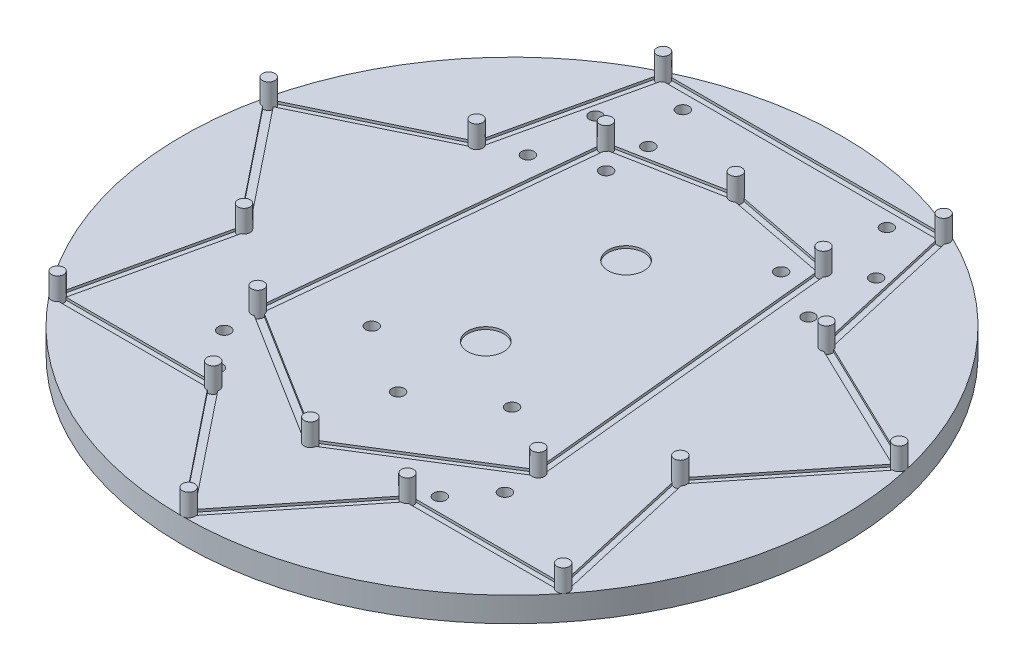
SolidWorks part; units mm, degrees
ref_plane "Front Plane" through (0, 0, 0) normal (0, 0, 1) x (1, 0, 0)
ref_plane "Top Plane" through (0, 0, 0) normal (0, 1, 0) x (1, 0, 0)
ref_plane "Right Plane" through (0, 0, 0) normal (1, 0, 0) x (0, 0, -1)
sketch "Sketch1" plane through (0, 0, 0) normal (0, 1, 0) x (1, 0, 0)
  circle A0 centre (0, 0) radius 132.5
  dimension "D1" = 265
extrude "Boss-Extrude1" add sketch "Sketch1" against normal blind 10
sketch "Sketch2" plane through (0, 0, 0) normal (0, 1, 0) x (1, 0, 0)
  line L0 (-102.3417, -81.6148) -> (102.3417, -81.6148)
  line L1 (102.3417, -81.6148) -> (56.7954, 117.9368)
  line L2 (56.7954, 117.9368) -> (-127.6181, 29.128)
  line L3 (-127.6181, 29.128) -> (0, -130.9)
  line L4 (0, -130.9) -> (127.6181, 29.128)
  line L5 (127.6181, 29.128) -> (-56.7954, 117.9368)
  line L6 (-56.7954, 117.9368) -> (-102.3417, -81.6148)
  line L7 (56.7954, 117.9368) -> (56.7954, 63.2344) construction
  line L8 (0, -130.9) -> (102.3417, -81.6148)
  line L9 (102.3417, -81.6148) -> (127.6181, 29.128)
  line L10 (127.6181, 29.128) -> (56.7954, 117.9368)
  line L11 (56.7954, 117.9368) -> (-56.7954, 117.9368)
  line L12 (-56.7954, 117.9368) -> (-127.6181, 29.128)
  line L13 (-127.6181, 29.128) -> (-102.3417, -81.6148)
  line L14 (-102.3417, -81.6148) -> (0, -130.9)
  line L15 (-56.7954, 117.9368) -> (-56.7954, 63.2344) construction
  line L16 (-56.7954, 90.5856) -> (56.7954, 90.5856) construction
  line L17 (-56.7954, 63.2344) -> (-56.7954, -119.7102) construction
  line L18 (0, -130.9) -> (0, -10.6142)
  line L19 (-35.4113, 73.5324) -> (-35.4113, 107.6388) construction
  line L20 (56.7954, -119.7102) -> (56.7954, 46.1812) construction
  line L21 (-56.7954, -46.1145) -> (56.7954, -46.1145)
  line L22 (56.7954, -10.6142) -> (-56.7954, -10.6142) construction
  line L23 (56.7954, -10.6142) -> (-56.7954, -81.6148) construction
  line L24 (0, -81.6148) -> (-56.7954, -46.1145) construction
  line L25 (56.7954, -81.6148) -> (-56.7954, -10.6142) construction
  line L26 (0, -81.6148) -> (56.7954, -46.1145) construction
  line L27 (56.7954, -46.1145) -> (0, -10.6142) construction
  line L28 (0, -10.6142) -> (-56.7954, -46.1145) construction
  line L29 (35.4113, 107.6388) -> (35.4113, 73.5324) construction
  circle A0 centre (0, 0) radius 130.9
  circle A1 centre (0, 0) radius 117.9368 construction
  circle A3 centre (0, 46.1812) radius 56.7954
  arc A4 (-0.0451, -132.5) -> (-54.8645, -120.6074) centre (-28.3977, -130.9) ccw
  arc A5 (54.8645, -120.6074) -> (0.0451, -132.5) centre (28.3977, -130.9) ccw
  circle A6 centre (0, 0) radius 132.5
  circle A7 centre (0, 0) radius 132.5 construction
  circle A9 centre (0, 46.1812) radius 7.27
  arc A10 (-56.7673, 119.7235) -> (56.7673, 119.7235) centre (0, 117.9368) ccw
  point P7 (35.4113, 90.5856)
  point P31 (0, -130.9)
  point P33 (-35.4113, 90.5856)
  point P40 (0, -46.1145)
  point P50 (-28.3977, -63.8647)
  point P54 (28.3977, -28.3643)
  point P55 (28.3977, -63.8647)
  point P56 (-28.3977, -28.3643)
  point P57 (-35.4113, 90.5856)
  point P60 (35.4113, 90.5856)
  dimension "D1" = 261.8
  dimension "D2" = 14.54
sketch "Sketch4" plane through (0, 0, 0) normal (0, 1, 0) x (1, 0, 0)
  line L4 (0, -130.9) -> (0, -10.6142) construction
  line L11 (-0.5, -123.3637) -> (-0.5, -46.6145)
  line L12 (0.5, -123.3637) -> (0.5, -46.6145)
  line L13 (56.7954, -46.1145) -> (-56.7954, -46.1145) construction
  line L14 (56.7954, -46.6145) -> (0.5, -46.6145)
  line L15 (56.7954, -45.6145) -> (0.5, -45.6145)
  line L16 (-0.5, -46.6145) -> (-56.7954, -46.6145)
  line L17 (-0.5, -45.6145) -> (-0.5, -11.112)
  line L18 (-0.5, -45.6145) -> (-56.7954, -45.6145)
  line L19 (0.5, -45.6145) -> (0.5, -11.112)
  circle A11 centre (0, 46.1812) radius 7.27
  circle A42 centre (0, 0) radius 130.9 construction
  arc A43 (54.8645, -120.6074) -> (0.0451, -132.5) centre (28.3977, -130.9) ccw construction
  arc A44 (54.2425, -119.1325) -> (0, -130.9) centre (28.3977, -130.9) ccw construction
  arc A45 (54.6976, -118.9253) -> (0.5, -123.3637) centre (28.3977, -130.9) ccw
  arc A46 (53.7875, -119.3397) -> (0.5, -130.9) centre (28.3977, -130.9) ccw
  arc A47 (53.7875, -119.3397) -> (54.6976, -118.9253) centre (54.2425, -119.1325) ccw
  arc A48 (-0.5, -130.9) -> (0.5, -130.9) centre (0, -130.9) ccw
  arc A49 (-0.5, -130.9) -> (0.5, -130.9) centre (0, -130.9) ccw
  arc A51 (56.7954, -46.6145) -> (56.7954, -45.6145) centre (56.7954, -46.1145) ccw
  arc A52 (-56.7954, -45.6145) -> (-56.7954, -46.6145) centre (-56.7954, -46.1145) ccw
  arc A53 (-54.2425, -119.1325) -> (0, -130.9) centre (-28.3977, -130.9) cw construction
  arc A54 (-53.7875, -119.3397) -> (-54.6976, -118.9253) centre (-54.2425, -119.1325) cw
  arc A55 (-54.6976, -118.9253) -> (-0.5, -123.3637) centre (-28.3977, -130.9) cw
  arc A56 (-53.7875, -119.3397) -> (-0.5, -130.9) centre (-28.3977, -130.9) cw
  arc A57 (-44.0241, 81.2675) -> (44.0241, 81.2675) centre (0, 46.1812) ccw
  arc A58 (0.5, -11.112) -> (44.6715, 82.059) centre (0, 46.1812) ccw
  arc A59 (56.7954, 117.9368) -> (-56.7954, 117.9368) centre (0, 117.9368) cw construction
  arc A60 (-57.2954, 117.9368) -> (-44.6715, 82.059) centre (0, 117.9368) ccw
  arc A61 (-56.2954, 117.9368) -> (-44.0241, 82.8505) centre (0, 117.9368) ccw
  arc A62 (-56.2954, 117.9368) -> (-57.2954, 117.9368) centre (-56.7954, 117.9368) ccw
  arc A63 (57.2954, 117.9368) -> (56.2954, 117.9368) centre (56.7954, 117.9368) ccw
  arc A64 (-56.7673, 119.7235) -> (56.7673, 119.7235) centre (0, 117.9368) ccw construction
  arc A65 (-44.0241, 81.2675) -> (44.0241, 81.2675) centre (0, 117.9368) ccw
  arc A66 (-44.6715, 82.059) -> (-0.5, -11.112) centre (0, 46.1812) ccw
  arc A67 (-43.3815, 82.059) -> (43.3815, 82.059) centre (0, 117.9368) ccw
  arc A68 (44.6715, 82.059) -> (57.2954, 117.9368) centre (0, 117.9368) ccw
  arc A69 (44.0241, 82.8505) -> (-44.0241, 82.8505) centre (0, 46.1812) ccw
  arc A70 (44.0241, 82.8505) -> (56.2954, 117.9368) centre (0, 117.9368) ccw
  arc A71 (43.3815, 82.059) -> (-43.3815, 82.059) centre (0, 46.1812) ccw
  circle A72 centre (0, 0) radius 132.5
  circle A73 centre (0, 46.1812) radius 56.2954
  point P0 (54.2425, -119.1325)
  point P1 (22.3771, -103.1479)
  point P16 (0, -70.7571)
  point P21 (0, -46.1145)
  point P42 (0, 61.1414)
  dimension "D1" = 1
  dimension "D2" = 1
  dimension "D3" = 1
  dimension "D4" = 1
  dimension "D5" = 1
  dimension "D6" = 14.54
extrude "Cut-Extrude2" cut sketch "Sketch4" against normal blind 1 contours A65 A73 A67 | A70 A69 A61 A62 A60 A66 L17 L18 A52 L16 L11 A55 A54 A56 A48 A46 A47 A45 L12 L14 A51 L15 L19 A58 A68 A63 A73 A57 A71 | A11
sketch "Sketch5" plane through (0, 0, 0) normal (0, 1, 0) x (1, 0, 0)
  line L0 (-102.3417, -81.6148) -> (102.3417, -81.6148) construction
  line L1 (0.2169, -131.3505) -> (102.5587, -82.0653)
  line L2 (102.8292, -81.7261) -> (128.1055, 29.0167)
  line L3 (128.009, 29.4397) -> (57.1863, 118.2486)
  line L4 (56.7954, 118.4368) -> (-56.7954, 118.4368)
  line L5 (-57.1863, 118.2486) -> (-128.009, 29.4397)
  line L6 (-128.1055, 29.0167) -> (-102.8292, -81.7261)
  line L7 (-102.5587, -82.0653) -> (-0.2169, -131.3505)
  line L9 (102.3417, -79.3678) -> (126.6431, 27.1035)
  line L10 (125.8613, 30.529) -> (57.7703, 115.9124)
  line L11 (54.6047, 117.4368) -> (-54.6047, 117.4368)
  line L15 (-101.7148, -81.1148) -> (-40.3419, -81.1148)
  line L16 (-100.1511, -82.1148) -> (-39.5444, -82.1148)
  line L17 (102.3417, -81.6148) -> (56.7954, 117.9368) construction
  line L19 (102.3417, -79.3678) -> (88.8555, -20.2807)
  line L20 (56.7954, 117.9368) -> (-127.6181, 29.128) construction
  line L22 (54.6047, 117.4368) -> (0, 91.1406)
  line L23 (-127.6181, 29.128) -> (0, -130.9) construction
  line L25 (-126.6431, 27.1035) -> (-88.8555, -20.2807)
  line L26 (0, -130.9) -> (127.6181, 29.128) construction
  line L28 (1.7568, -129.499) -> (39.5444, -82.1148)
  line L29 (127.6181, 29.128) -> (-56.7954, 117.9368) construction
  line L31 (125.8613, 30.529) -> (71.2566, 56.8252)
  line L32 (-102.3417, -81.6148) -> (-56.7954, 117.9368) construction
  line L33 (-102.3417, -79.3678) -> (-88.8555, -20.2807)
  line L36 (-57.7703, 115.9124) -> (-125.8613, 30.529)
  line L37 (-56.7047, 117.2486) -> (-57.0518, 116.8133) [skipped]
  line L38 (56.4474, 117.2143) -> (1.1524, 90.5856)
  line L39 (126.8362, 28.9495) -> (71.5412, 55.5782)
  line L40 (1.7568, -129.499) -> (100.1511, -82.1148)
  line L41 (101.7148, -81.1148) -> (88.058, -21.2807)
  line L42 (0.2169, -130.2406) -> (0.7185, -129.999) [skipped]
  line L43 (0, -130.0981) -> (38.2654, -82.1148)
  line L44 (-101.7148, -81.1148) -> (-88.058, -21.2807)
  line L45 (-100.1511, -82.1148) -> (-1.7568, -129.499)
  line L46 (-101.6909, -81.3733) -> (-101.1894, -81.6148) [skipped]
  line L47 (-126.6431, 27.1035) -> (-102.3417, -79.3678)
  line L48 (-127.0234, 28.7698) -> (-126.8996, 28.227) [skipped]
  line L49 (-126.8362, 28.9495) -> (-88.5709, -19.0337)
  line L50 (88.8555, -20.2807) -> (126.6431, 27.1035)
  line L51 (87.7734, -20.0337) -> (70.3888, 56.1332)
  line L52 (88.5709, -19.0337) -> (126.8362, 28.9495)
  line L53 (88.5709, -19.0337) -> (71.5412, 55.5782)
  line L54 (40.3419, -81.1148) -> (88.058, -21.2807)
  line L55 (39.5444, -82.1148) -> (100.1511, -82.1148)
  line L56 (39.0628, -81.1148) -> (87.7734, -20.0337)
  line L57 (40.3419, -81.1148) -> (101.7148, -81.1148)
  line L58 (-38.2654, -82.1148) -> (38.2654, -82.1148)
  line L59 (-39.5444, -82.1148) -> (-1.7568, -129.499)
  line L60 (-39.0628, -81.1148) -> (39.0628, -81.1148)
  line L61 (-38.2654, -82.1148) -> (0, -130.0981)
  line L62 (-87.7734, -20.0337) -> (-70.3888, 56.1332)
  line L63 (-88.058, -21.2807) -> (-40.3419, -81.1148)
  line L64 (-87.7734, -20.0337) -> (-39.0628, -81.1148)
  line L65 (-88.5709, -19.0337) -> (-71.5412, 55.5782)
  line L66 (-71.5412, 55.5782) -> (-126.8362, 28.9495)
  line L67 (-70.1042, 57.3802) -> (-56.4474, 117.2143)
  line L68 (-71.2566, 56.8252) -> (-125.8613, 30.529)
  line L69 (-71.2566, 56.8252) -> (-57.7703, 115.9124)
  line L70 (0, 90.0307) -> (-70.3888, 56.1332)
  line L71 (0, 91.1406) -> (-54.6047, 117.4368)
  line L72 (-1.1524, 90.5856) -> (-70.1042, 57.3802)
  line L73 (-1.1524, 90.5856) -> (-56.4474, 117.2143)
  line L74 (70.3888, 56.1332) -> (0, 90.0307)
  line L75 (71.2566, 56.8252) -> (57.7703, 115.9124)
  line L76 (70.1042, 57.3802) -> (1.1524, 90.5856)
  line L77 (70.1042, 57.3802) -> (56.4474, 117.2143)
  circle A0 centre (0, 0) radius 132.5
  circle A2 centre (0, 0) radius 117.4368 construction
  arc A3 (-102.8292, -81.7261) -> (-102.5587, -82.0653) centre (-102.3417, -81.6148) ccw
  arc A5 (-128.009, 29.4397) -> (-128.1055, 29.0167) centre (-127.6181, 29.128) ccw
  arc A8 (-57.1863, 118.2486) -> (-56.7954, 118.4368) centre (-56.7954, 117.9368) cw
  arc A9 (56.7954, 118.4368) -> (57.1863, 118.2486) centre (56.7954, 117.9368) cw
  arc A12 (128.1055, 29.0167) -> (128.009, 29.4397) centre (127.6181, 29.128) ccw
  arc A13 (102.8292, -81.7261) -> (102.5587, -82.0653) centre (102.3417, -81.6148) cw
  arc A16 (-0.2169, -131.3505) -> (0.2169, -131.3505) centre (0, -130.9) ccw
  arc A18 (102.5587, -82.0653) -> (102.8292, -81.7261) centre (102.3417, -81.6148) ccw
  arc A20 (57.1863, 118.2486) -> (56.7954, 118.4368) centre (56.7954, 117.9368) ccw
  arc A21 (57.1863, 118.2486) -> (56.7954, 118.4368) centre (56.7954, 117.9368) ccw
  arc A22 (-128.009, 29.4397) -> (-128.1055, 29.0167) centre (-127.6181, 29.128) ccw
  arc A23 (-128.009, 29.4397) -> (-128.1055, 29.0167) centre (-127.6181, 29.128) ccw
  arc A24 (-0.2169, -131.3505) -> (0.2169, -131.3505) centre (0, -130.9) ccw
  arc A25 (-0.2169, -131.3505) -> (0.2169, -131.3505) centre (0, -130.9) ccw
  arc A26 (128.1055, 29.0167) -> (128.009, 29.4397) centre (127.6181, 29.128) ccw
  arc A27 (128.1055, 29.0167) -> (128.009, 29.4397) centre (127.6181, 29.128) ccw
  arc A28 (-56.7954, 118.4368) -> (-57.1863, 118.2486) centre (-56.7954, 117.9368) ccw
  arc A29 (-56.2954, 117.9368) -> (-57.2954, 117.9368) centre (-56.7954, 117.9368) ccw construction
  arc A30 (-102.8292, -81.7261) -> (-102.5587, -82.0653) centre (-102.3417, -81.6148) ccw
  arc A31 (-56.7954, 118.4368) -> (-57.1863, 118.2486) centre (-56.7954, 117.9368) ccw
  arc A32 (102.5587, -82.0653) -> (102.8292, -81.7261) centre (102.3417, -81.6148) ccw
  arc A33 (-102.8292, -81.7261) -> (-102.5587, -82.0653) centre (-102.3417, -81.6148) ccw
  point P45 (0, -130.345)
  point P52 (0, -81.6148)
  point P57 (79.5686, 18.161)
  point P65 (-35.4113, 73.5324)
  point P73 (-63.809, -50.886)
  point P81 (63.809, -50.886)
  point P89 (35.4113, 73.5324)
  point P100 (-79.5686, 18.161)
  arc M31 (-44.0241, 82.8505) -> (44.0241, 82.8505) centre (0, 46.1812) cw
  arc M32 (44.0241, 82.8505) -> (56.2954, 117.9368) centre (0, 117.9368) ccw
  arc M33 (56.2954, 117.9368) -> (57.2954, 117.9368) centre (56.7954, 117.9368) cw
  arc M34 (57.2954, 117.9368) -> (44.6715, 82.059) centre (0, 117.9368) cw
  arc M35 (44.6715, 82.059) -> (0.5, -11.112) centre (0, 46.1812) cw
  line M40 (0.5, -46.6145) -> (0.5, -123.3637)
  arc M41 (0.5, -123.3637) -> (54.6976, -118.9253) centre (28.3977, -130.9) cw
  arc M43 (53.7875, -119.3397) -> (0.5, -130.9) centre (28.3977, -130.9) ccw
  arc M44 (0.5, -130.9) -> (-0.5, -130.9) centre (0, -130.9) cw
  arc M45 (-0.5, -130.9) -> (-53.7875, -119.3397) centre (-28.3977, -130.9) ccw
  arc M47 (-54.6976, -118.9253) -> (-0.5, -123.3637) centre (-28.3977, -130.9) cw
  line M48 (-0.5, -123.3637) -> (-0.5, -46.6145)
  arc M53 (-0.5, -11.112) -> (-44.6715, 82.059) centre (0, 46.1812) cw
  arc M54 (-44.6715, 82.059) -> (-57.2954, 117.9368) centre (0, 117.9368) cw
  arc M55 (-57.2954, 117.9368) -> (-56.2954, 117.9368) centre (-56.7954, 117.9368) cw
  arc M56 (-56.2954, 117.9368) -> (-44.0241, 82.8505) centre (0, 117.9368) ccw
  dimension "D2" = 0.5
  dimension "D1" = 1
extrude "Cut-Extrude3" cut sketch "Sketch5" against normal blind 1 contours A13 L2 A12 L3 L77 L76 L74 L51 L56 L60 L58 L43 L28 L55 L40 L1 L57 L54 L41 L19 L50 L9 L52 L53 L39 L31 L75 L10 M33 M34 M35 M40 M41 | L43 L1 L40 L28 M43 M44 | L61 L59 L45 L7 M45 M44 | L5 A5 L6 A3 L7 L45 L16 L59 L61 L58 L60 L64 L62 L70 L72 L67 L44 L63 L15 L47 L25 L33 L66 L65 L49 L69 L68 L36 M47 M48 M53 M54 M55 | L76 L38 L22 L71 L73 L72 L70 L74 M35 M31 M53 | L73 L71 L11 L22 L38 L4 M31 M32 M33 M55 M56
sketch "Sketch6" plane through (0, -1, 0) normal (0, 1, 0) x (1, 0, 0)
  line L0 (0, -130.9) -> (127.6181, 29.128) construction
  line L1 (127.6181, 29.128) -> (-56.7954, 117.9368) construction
  line L2 (-56.7954, 117.9368) -> (-102.3417, -81.6148) construction
  line L3 (-102.3417, -81.6148) -> (0, -130.9) construction
  line L4 (0, -130.9) -> (102.3417, -81.6148) construction
  line L5 (102.3417, -81.6148) -> (127.6181, 29.128) construction
  line L6 (127.6181, 29.128) -> (56.7954, 117.9368) construction
  line L7 (56.7954, 117.9368) -> (-56.7954, 117.9368) construction
  line L8 (-56.7954, 117.9368) -> (-127.6181, 29.128) construction
  line L9 (-127.6181, 29.128) -> (-102.3417, -81.6148) construction
  line L10 (-102.3417, -81.6148) -> (102.3417, -81.6148) construction
  line L11 (102.3417, -81.6148) -> (56.7954, 117.9368) construction
  line L12 (56.7954, 117.9368) -> (-127.6181, 29.128) construction
  line L13 (-127.6181, 29.128) -> (0, -130.9) construction
  circle A1 centre (-127.6181, 29.128) radius 2.5
  circle A2 centre (-102.3417, -81.6148) radius 2.5
  circle A3 centre (0, -130.9) radius 2.5
  circle A4 centre (102.3417, -81.6148) radius 2.5
  circle A5 centre (127.6181, 29.128) radius 2.5
  circle A6 centre (56.7954, 117.9368) radius 2.5
  circle A7 centre (-56.7954, 117.9368) radius 2.5
  circle A8 centre (39.3036, -81.6148) radius 2.5
  circle A9 centre (-39.3036, -81.6148) radius 2.5
  circle A10 centre (88.3144, -20.1572) radius 2.5
  circle A11 centre (-88.3144, -20.1572) radius 2.5
  circle A12 centre (70.8227, 56.4792) radius 2.5
  circle A13 centre (-70.8227, 56.4792) radius 2.5
  arc A15 (42.4068, 83.9618) -> (-42.4068, 83.9618) centre (0, 46.1812) ccw
  circle A16 centre (0, 46.1812) radius 57.2954
  circle A17 centre (44.0284, 82.059) radius 2.5
  circle A18 centre (-44.0284, 82.059) radius 2.5
  circle A19 centre (0, 90.5856) radius 2.5
  arc A20 (-56.7404, 115.4374) -> (-45.5646, 84.0313) centre (0, 117.9368) ccw
  arc A21 (-42.4068, 80.1562) -> (42.4068, 80.1562) centre (0, 117.9368) ccw
  arc A22 (45.5646, 84.0313) -> (56.7404, 115.4374) centre (0, 117.9368) ccw
  arc A23 (-45.5646, 80.0867) -> (45.5646, 80.0867) centre (0, 46.1812) ccw
  circle A24 centre (56.7954, -46.1145) radius 2.5
  circle A25 centre (0, -81.6148) radius 2.5
  circle A26 centre (-56.7954, -46.1145) radius 2.5
  point P42 (44.0284, 82.059)
  point P45 (-44.0284, 82.059)
  dimension "D1" = 5
  dimension "D2" = 5
  dimension "D3" = 5
  dimension "D4" = 5
  dimension "D5" = 5
  dimension "D6" = 5
  dimension "D7" = 5
  dimension "D8" = 0.5
  dimension "D9" = 5
  dimension "D10" = 5
  dimension "D11" = 5
  dimension "D12" = 5
  dimension "D13" = 5
  dimension "D14" = 5
  dimension "D15" = 5
  dimension "D16" = 5
  dimension "D17" = 5
  dimension "D18" = 56.7954
  dimension "D20" = 44.0284
  dimension "D21" = 5
  dimension "D22" = 5
  dimension "D23" = 5
  dimension "D19" = 44.0284
extrude "Boss-Extrude2" add sketch "Sketch6" along normal blind 10 contours A1 | A13 | A11 | A2 | A9 | A3 | A8 | A4 | A10 | A5 | A12 | A17 | A6 | A19 | A18 | A7 | A26 | A25 | A24
sketch "Sketch7" plane through (0, -10, 0) normal (0, -1, 0) x (1, 0, 0)
  circle A0 centre (0, 0) radius 133.4
extrude "Boss-Extrude3" add sketch "Sketch7" against normal blind 10
sketch "Sketch8" plane through (0, 0, 0) normal (0, 1, 0) x (1, 0, 0)
  line L0 (0, -130.9) -> (39.3036, -81.6148) construction
  line L1 (-1.1727, -129.9648) -> (38.1309, -80.6796)
  line L2 (1.1727, -131.8352) -> (40.4764, -82.55)
  line L3 (39.3036, -81.6148) -> (102.3417, -81.6148) construction
  line L4 (39.3036, -80.1148) -> (102.3417, -80.1148)
  line L5 (39.3036, -83.1148) -> (102.3417, -83.1148)
  line L6 (102.3417, -81.6148) -> (88.3144, -20.1572) construction
  line L7 (100.8793, -81.9486) -> (86.852, -20.491)
  line L8 (103.8041, -81.281) -> (89.7768, -19.8234)
  line L9 (88.3144, -20.1572) -> (127.6181, 29.128) construction
  line L10 (87.1417, -19.222) -> (126.4453, 30.0632)
  line L11 (89.4872, -21.0924) -> (128.7908, 28.1928)
  line L12 (127.6181, 29.128) -> (70.8227, 56.4792) construction
  line L13 (126.9672, 27.7765) -> (70.1719, 55.1278)
  line L14 (128.2689, 30.4794) -> (71.4735, 57.8307)
  line L15 (70.8227, 56.4792) -> (56.7954, 117.9368) construction
  line L16 (69.3603, 56.1454) -> (55.333, 117.603)
  line L17 (72.2851, 56.813) -> (58.2578, 118.2706)
  line L18 (56.7954, 117.9368) -> (-56.7954, 117.9368) construction
  line L19 (56.7954, 116.4368) -> (-56.7954, 116.4368)
  line L20 (56.7954, 119.4368) -> (-56.7954, 119.4368)
  line L21 (-56.7954, 117.9368) -> (-70.8227, 56.4792) construction
  line L22 (-55.333, 117.603) -> (-69.3603, 56.1454)
  line L23 (-58.2578, 118.2706) -> (-72.2851, 56.813)
  line L24 (-70.8227, 56.4792) -> (-127.6181, 29.128) construction
  line L25 (-70.1719, 55.1278) -> (-126.9672, 27.7765)
  line L26 (-71.4735, 57.8307) -> (-128.2689, 30.4794)
  line L27 (-127.6181, 29.128) -> (-88.3144, -20.1572) construction
  line L28 (-126.4453, 30.0632) -> (-87.1417, -19.222)
  line L29 (-128.7908, 28.1928) -> (-89.4872, -21.0924)
  line L30 (-88.3144, -20.1572) -> (-102.3417, -81.6148) construction
  line L31 (-86.852, -20.491) -> (-100.8793, -81.9486)
  line L32 (-89.7768, -19.8234) -> (-103.8041, -81.281)
  line L33 (-102.3417, -81.6148) -> (-39.3036, -81.6148) construction
  line L34 (-102.3417, -80.1148) -> (-39.3036, -80.1148)
  line L35 (-102.3417, -83.1148) -> (-39.3036, -83.1148)
  line L36 (-39.3036, -81.6148) -> (0, -130.9) construction
  line L37 (-38.1309, -80.6796) -> (1.1727, -129.9648)
  line L38 (-40.4764, -82.55) -> (-1.1727, -131.8352)
  line L39 (0, -81.6148) -> (56.7954, -46.1145) construction
  line L40 (-0.795, -80.3428) -> (56.0003, -44.8425)
  line L41 (0.795, -82.8868) -> (57.5904, -47.3865)
  line L42 (0, -81.6148) -> (-56.7954, -46.1145) construction
  line L43 (-0.795, -82.8868) -> (-57.5904, -47.3865)
  line L44 (0.795, -80.3428) -> (-56.0003, -44.8425)
  line L45 (56.7954, -46.1145) -> (44.0284, 82.059) construction
  line L46 (55.3028, -46.2632) -> (42.5358, 81.9103)
  line L47 (58.288, -45.9658) -> (45.521, 82.2077)
  line L48 (44.0284, 82.059) -> (0, 90.5856) construction
  line L49 (43.7432, 80.5864) -> (-0.2852, 89.113)
  line L50 (44.3136, 83.5316) -> (0.2852, 92.0582)
  line L51 (-44.0284, 82.059) -> (0, 90.5856) construction
  line L52 (-44.3136, 83.5316) -> (-0.2852, 92.0582)
  line L53 (-43.7432, 80.5864) -> (0.2852, 89.113)
  line L54 (-44.0284, 82.059) -> (-56.7954, -46.1145) construction
  line L55 (-42.5358, 81.9103) -> (-55.3028, -46.2632)
  line L56 (-45.521, 82.2077) -> (-58.288, -45.9658)
  arc A0 (-1.1727, -129.9648) -> (1.1727, -131.8352) centre (0, -130.9) ccw
  arc A1 (40.4764, -82.55) -> (38.1309, -80.6796) centre (39.3036, -81.6148) ccw
  arc A2 (39.3036, -80.1148) -> (39.3036, -83.1148) centre (39.3036, -81.6148) ccw
  arc A3 (102.3417, -83.1148) -> (102.3417, -80.1148) centre (102.3417, -81.6148) ccw
  arc A4 (100.8793, -81.9486) -> (103.8041, -81.281) centre (102.3417, -81.6148) ccw
  arc A5 (89.7768, -19.8234) -> (86.852, -20.491) centre (88.3144, -20.1572) ccw
  arc A6 (87.1417, -19.222) -> (89.4872, -21.0924) centre (88.3144, -20.1572) ccw
  arc A7 (128.7908, 28.1928) -> (126.4453, 30.0632) centre (127.6181, 29.128) ccw
  arc A8 (126.9672, 27.7765) -> (128.2689, 30.4794) centre (127.6181, 29.128) ccw
  arc A9 (71.4735, 57.8307) -> (70.1719, 55.1278) centre (70.8227, 56.4792) ccw
  arc A10 (69.3603, 56.1454) -> (72.2851, 56.813) centre (70.8227, 56.4792) ccw
  arc A11 (58.2578, 118.2706) -> (55.333, 117.603) centre (56.7954, 117.9368) ccw
  arc A12 (56.7954, 116.4368) -> (56.7954, 119.4368) centre (56.7954, 117.9368) ccw
  arc A13 (-56.7954, 119.4368) -> (-56.7954, 116.4368) centre (-56.7954, 117.9368) ccw
  arc A14 (-55.333, 117.603) -> (-58.2578, 118.2706) centre (-56.7954, 117.9368) ccw
  arc A15 (-72.2851, 56.813) -> (-69.3603, 56.1454) centre (-70.8227, 56.4792) ccw
  arc A16 (-70.1719, 55.1278) -> (-71.4735, 57.8307) centre (-70.8227, 56.4792) ccw
  arc A17 (-128.2689, 30.4794) -> (-126.9672, 27.7765) centre (-127.6181, 29.128) ccw
  arc A18 (-126.4453, 30.0632) -> (-128.7908, 28.1928) centre (-127.6181, 29.128) ccw
  arc A19 (-89.4872, -21.0924) -> (-87.1417, -19.222) centre (-88.3144, -20.1572) ccw
  arc A20 (-86.852, -20.491) -> (-89.7768, -19.8234) centre (-88.3144, -20.1572) ccw
  arc A21 (-103.8041, -81.281) -> (-100.8793, -81.9486) centre (-102.3417, -81.6148) ccw
  arc A22 (-102.3417, -80.1148) -> (-102.3417, -83.1148) centre (-102.3417, -81.6148) ccw
  arc A23 (-39.3036, -83.1148) -> (-39.3036, -80.1148) centre (-39.3036, -81.6148) ccw
  arc A24 (-38.1309, -80.6796) -> (-40.4764, -82.55) centre (-39.3036, -81.6148) ccw
  arc A25 (-1.1727, -131.8352) -> (1.1727, -129.9648) centre (0, -130.9) ccw
  arc A26 (-0.795, -80.3428) -> (0.795, -82.8868) centre (0, -81.6148) ccw
  arc A27 (57.5904, -47.3865) -> (56.0003, -44.8425) centre (56.7954, -46.1145) ccw
  arc A28 (-0.795, -82.8868) -> (0.795, -80.3428) centre (0, -81.6148) ccw
  arc A29 (-56.0003, -44.8425) -> (-57.5904, -47.3865) centre (-56.7954, -46.1145) ccw
  arc A30 (55.3028, -46.2632) -> (58.288, -45.9658) centre (56.7954, -46.1145) ccw
  arc A31 (45.521, 82.2077) -> (42.5358, 81.9103) centre (44.0284, 82.059) ccw
  arc A32 (43.7432, 80.5864) -> (44.3136, 83.5316) centre (44.0284, 82.059) ccw
  arc A33 (0.2852, 92.0582) -> (-0.2852, 89.113) centre (0, 90.5856) ccw
  arc A34 (-44.3136, 83.5316) -> (-43.7432, 80.5864) centre (-44.0284, 82.059) ccw
  arc A35 (0.2852, 89.113) -> (-0.2852, 92.0582) centre (0, 90.5856) ccw
  arc A36 (-42.5358, 81.9103) -> (-45.521, 82.2077) centre (-44.0284, 82.059) ccw
  arc A37 (-58.288, -45.9658) -> (-55.3028, -46.2632) centre (-56.7954, -46.1145) ccw
  circle A38 centre (0, 46.1812) radius 7.27
  circle A39 centre (0, -10.6142) radius 7.27
  point P4 (19.6518, -106.2574)
  point P9 (70.8227, -81.6148)
  point P17 (95.3281, -50.886)
  point P25 (107.9663, 4.4854)
  point P33 (99.2204, 42.8036)
  point P41 (63.809, 87.208)
  point P49 (0, 117.9368)
  point P57 (-63.809, 87.208)
  point P65 (-99.2204, 42.8036)
  point P73 (-107.9663, 4.4854)
  point P81 (-95.3281, -50.886)
  point P89 (-70.8227, -81.6148)
  point P97 (-19.6518, -106.2574)
  point P108 (28.3977, -63.8647)
  point P113 (-28.3977, -63.8647)
  point P121 (50.4119, 17.9723)
  point P129 (22.0142, 86.3223)
  point P137 (-22.0142, 86.3223)
  point P145 (-50.4119, 17.9723)
  circle M5 centre (-44.0284, 82.059) radius 2.5
  circle M7 centre (-56.7954, 117.9368) radius 2.5
  circle M9 centre (-127.6181, 29.128) radius 2.5
  circle M11 centre (-102.3417, -81.6148) radius 2.5
  circle M13 centre (0, -130.9) radius 2.5
  circle M15 centre (102.3417, -81.6148) radius 2.5
  circle M17 centre (127.6181, 29.128) radius 2.5
  circle M19 centre (56.7954, 117.9368) radius 2.5
  circle M20 centre (-70.8227, 56.4792) radius 2.5
  circle M21 centre (0, 90.5856) radius 2.5
  circle M22 centre (44.0284, 82.059) radius 2.5
  circle M23 centre (70.8227, 56.4792) radius 2.5
  circle M24 centre (88.3144, -20.1572) radius 2.5
  circle M25 centre (39.3036, -81.6148) radius 2.5
  circle M26 centre (-39.3036, -81.6148) radius 2.5
  circle M27 centre (-88.3144, -20.1572) radius 2.5
  circle M38 centre (0, -81.6148) radius 2.5
  circle M39 centre (56.7954, -46.1145) radius 2.5
  circle M40 centre (-56.7954, -46.1145) radius 2.5
  dimension "D3" = 14.54
  dimension "D4" = 14.54
  dimension "D1" = 3
  dimension "D2" = 3
extrude "Cut-Extrude4" cut sketch "Sketch8" against normal blind 1 contours L38 L37 M26 M13 | L2 L1 M13 M25 | L5 L4 M25 M15 | L8 L7 M15 M24 | L11 L10 M24 M17 | L14 L13 M17 M23 | L17 L16 M23 M19 | L20 L19 M19 M7 | L23 L22 M7 M20 | L26 L25 M20 M9 | L29 L28 M9 M27 | L32 L31 M27 M11 | L35 L34 M11 M26 | L44 L43 M38 M40 | L41 L40 M38 M39 | L56 L55 M5 M40 | L53 L52 M5 M21 | L50 L49 M22 M21 | L47 L46 M39 M22 | A38 | A39
sketch "Sketch9" plane through (0, 0, 0) normal (0, 1, 0) x (1, 0, 0)
  line L0 (0, -130.9) -> (127.6181, 29.128) construction
  line L1 (-127.6181, 29.128) -> (0, -130.9) construction
  line L2 (127.6181, 29.128) -> (-56.7954, 117.9368) construction
  line L3 (56.7954, 117.9368) -> (-127.6181, 29.128) construction
  line L4 (56.7954, -10.6142) -> (-56.7954, -81.6148) construction
  line L5 (-56.7954, 63.2344) -> (-56.7954, -119.7102) construction
  line L6 (56.7954, -81.6148) -> (-56.7954, -10.6142) construction
  line L7 (56.7954, -119.7102) -> (56.7954, 46.1812) construction
  circle A0 centre (45.1223, -74.3185) radius 2.5
  circle A1 centre (56.7954, -59.6808) radius 2.5
  circle A2 centre (-45.1223, -74.3185) radius 2.5
  circle A3 centre (-56.7954, -59.6808) radius 2.5
  circle A4 centre (-35.4113, 73.5324) radius 2.5
  circle A5 centre (-56.7954, 63.2344) radius 2.5
  circle A6 centre (-35.4113, 90.5856) radius 2.5
  circle A7 centre (-56.7954, 90.5856) radius 2.5
  circle A8 centre (35.4113, 90.5856) radius 2.5
  circle A9 centre (56.7954, 90.5856) radius 2.5
  circle A10 centre (56.7954, 63.2344) radius 2.5
  circle A11 centre (41.2934, 110.4715) radius 2.5
  circle A12 centre (0, 0) radius 117.9368 construction
  circle A13 centre (-41.2934, 110.4715) radius 2.5
  circle A14 centre (35.4113, 73.5324) radius 2.5
  circle A15 centre (28.3977, -28.3643) radius 2.5
  circle A16 centre (0, -46.1145) radius 2.5
  circle A17 centre (-28.3977, -28.3643) radius 2.5
  dimension "D1" = 5
  dimension "D2" = 5
  dimension "D3" = 5
  dimension "D4" = 5
  dimension "D5" = 5
  dimension "D6" = 5
  dimension "D7" = 5
  dimension "D8" = 5
  dimension "D9" = 5
  dimension "D10" = 5
  dimension "D11" = 5
  dimension "D12" = 5
  dimension "D13" = 5
  dimension "D14" = 5
  dimension "D15" = 5
  dimension "D16" = 5
  dimension "D17" = 5
extrude "Cut-Extrude5" cut sketch "Sketch9" against normal blind 10
sketch "Sketch10" plane through (0, -10, 0) normal (0, -1, 0) x (1, 0, 0)
  line L0 (127.6181, -29.128) -> (-56.7954, -117.9368) construction
  line L3 (-127.6181, -29.128) -> (0, 130.9) construction
  line L6 (56.7954, 46.1145) -> (0, 10.6142) construction
  line L8 (0, 130.9) -> (0, 10.6142) construction
  line L9 (56.7954, 81.6148) -> (-56.7954, 10.6142) construction
  line L10 (0, 130.9) -> (127.6181, -29.128) construction
  line L13 (56.7954, 10.6142) -> (-56.7954, 81.6148) construction
  line L21 (0, 3.3442) -> (0, 17.8842) construction
  line L22 (-5.1407, 15.7549) -> (5.1407, 5.4735) construction
  line L23 (0, 10.6142) -> (-56.7954, 46.1145) construction
  arc A19 (-56.7954, 59.6808) -> (0, 92.2089) centre (0, 26.3613) cw construction
  arc A24 (-3.5151, 94.1178) -> (-43.8702, 78.1175) centre (0, 26.3613) ccw
  arc A34 (-3.4099, 90.1178) -> (-41.2059, 75.1321) centre (0, 26.3613) ccw
  arc A56 (0, 92.2089) -> (56.7954, 59.6808) centre (0, 26.3613) cw construction
  arc A57 (56.6632, 63.6787) -> (48.9904, 73.3) centre (0, 26.3613) ccw
  arc A58 (53.2663, 61.5638) -> (46.1727, 70.4589) centre (0, 26.3613) ccw
  arc A61 (28.3977, 28.3643) -> (-28.3977, 28.3643) centre (0, 14.5233) ccw construction
  arc A62 (28.462, 32.3638) -> (3.567, 47.9246) centre (0, 14.5233) ccw
  arc A63 (24.9626, 30.4138) -> (3.3473, 43.9246) centre (0, 14.5233) ccw
  arc A66 (-7.27, -46.1812) -> (-28.3977, 28.3643) centre (23.8412, 2.9031) cw construction
  arc A67 (-31.6457, 26.0297) -> (-11.967, -45.3815) centre (23.8412, 2.9031) ccw
  arc A68 (-27.9978, 24.3844) -> (-8.8882, -42.6766) centre (23.8412, 2.9031) ccw
  arc A71 (56.7954, 59.6808) -> (5.1407, 5.4735) centre (23.2049, 39.9747) cw construction
  arc A72 (-8.8882, -42.6766) -> (-6.0557, -42.1586) centre (-7.7217, -41.052) ccw
  arc A77 (35.4113, -90.5856) -> (2.664, -67.5077) centre (16.9148, -82.059) ccw construction
  arc A78 (-56.7954, -63.2344) -> (-41.2934, -110.4715) centre (-18.7466, -76.91) ccw construction
  arc A79 (-59.7371, -65.9448) -> (-59.7371, -87.8752) centre (-18.7466, -76.91) ccw
  arc A80 (-55.9149, -67.1363) -> (-55.9149, -86.6837) centre (-18.7466, -76.91) ccw
  arc A83 (56.7954, -63.2344) -> (41.2934, -110.4715) centre (18.7466, -76.91) cw construction
  arc A88 (45.2691, -110.0312) -> (57.3386, -94.5486) centre (18.7466, -76.91) ccw
  arc A94 (5.1407, 5.4735) -> (56.7954, -63.2344) centre (-80.2432, -112.4892) cw construction
  arc A95 (57.4591, -59.2898) -> (15.6676, -0.2697) centre (-80.2432, -112.4892) ccw
  arc A96 (53.711, -60.6876) -> (4.1246, 3.7398) centre (-80.2432, -112.4892) ccw
  arc A99 (38.4749, -88.0137) -> (38.4749, -76.1043) centre (16.9148, -82.059) ccw
  arc A100 (34.6992, -86.6495) -> (34.6992, -77.4685) centre (16.9148, -82.059) ccw
  arc A103 (-35.4113, -90.5856) -> (-7.27, -46.1812) centre (0.2382, -82.059) cw construction
  arc A108 (-7.27, -46.1812) -> (2.664, -67.5077) centre (-6.0635, -58.5961) ccw construction
  arc A110 (-8.558, -48.4241) -> (1.2647, -66.0788) centre (-6.0635, -58.5961) ccw
  arc A113 (56.7673, -119.7235) -> (-56.7673, -119.7235) centre (0, -117.9368) ccw construction
  arc A115 (-6.3645, -49.6949) -> (-6.0557, -42.1586) centre (0, -46.1812) ccw
  arc A116 (-19.6847, -53.7033) -> (-32.5244, -70.7637) centre (0.2382, -82.059) ccw
  arc A117 (-19.6847, -53.7033) -> (4.0634, -68.9366) centre (-6.0635, -58.5961) ccw
  arc A118 (-38.0239, -87.5567) -> (-34.0896, -86.8103) centre (-35.4113, -90.5856) ccw
  arc A119 (-11.967, -45.3815) -> (-36.3707, -69.6491) centre (0.2382, -82.059) ccw
  arc A120 (-34.0896, -77.3077) -> (-32.5244, -70.7637) centre (-35.4113, -73.5324) ccw
  arc A121 (34.6992, -86.6495) -> (38.4749, -88.0137) centre (35.4113, -90.5856) ccw
  arc A122 (38.4749, -76.1043) -> (35.4454, -69.5326) centre (35.4113, -73.5324) ccw
  arc A123 (-38.0239, -76.5614) -> (-38.0239, -87.5567) centre (0.2382, -82.059) ccw
  arc A124 (-34.0896, -77.3077) -> (-34.0896, -86.8103) centre (0.2382, -82.059) ccw
  arc A125 (-36.3707, -69.6491) -> (-38.0239, -76.5614) centre (-35.4113, -73.5324) ccw
  arc A126 (31.9559, -71.5175) -> (4.0634, -68.9366) centre (16.9148, -82.059) ccw
  arc A127 (35.4454, -69.5326) -> (1.2647, -66.0788) centre (16.9148, -82.059) ccw
  arc A128 (31.9559, -71.5175) -> (34.6992, -77.4685) centre (35.4113, -73.5324) ccw
  arc A129 (-6.3645, -49.6949) -> (-8.558, -48.4241) centre (-8.5182, -50.8839) ccw
  arc A130 (-27.9978, 24.3844) -> (-24.9626, 30.4138) centre (-28.3977, 28.3643) ccw
  arc A131 (3.567, 47.9246) -> (-3.567, 47.9246) centre (0, 46.1145) ccw
  arc A132 (24.9626, 30.4138) -> (28.462, 32.3638) centre (28.3977, 28.3643) ccw
  arc A133 (-28.462, 32.3638) -> (-31.6457, 26.0297) centre (-28.3977, 28.3643) ccw
  arc A134 (-3.3473, 43.9246) -> (-24.9626, 30.4138) centre (0, 14.5233) ccw
  arc A135 (-3.567, 47.9246) -> (-28.462, 32.3638) centre (0, 14.5233) ccw
  arc A136 (-3.3473, 43.9246) -> (3.3473, 43.9246) centre (0, 46.1145) ccw
  arc A137 (-41.2934, -110.4715) -> (41.2934, -110.4715) centre (0, -17.5817) ccw construction
  arc A138 (-38.8859, -113.6658) -> (38.8859, -113.6658) centre (0, -17.5817) ccw
  arc A142 (-37.3234, -109.983) -> (-42.8961, -106.8066) centre (-41.2934, -110.4715) ccw
  arc A143 (-53.6324, -93.0341) -> (-55.9149, -86.6837) centre (-56.7954, -90.5856) ccw
  arc A144 (-55.9149, -67.1363) -> (-59.7371, -65.9448) centre (-56.7954, -63.2344) ccw
  arc A145 (38.8859, -113.6658) -> (45.2691, -110.0312) centre (41.2934, -110.4715) ccw
  arc A146 (55.9149, -86.6837) -> (53.6324, -93.0341) centre (56.7954, -90.5856) ccw
  arc A147 (59.7371, -65.9448) -> (57.4591, -59.2898) centre (56.7954, -63.2344) ccw
  arc A148 (60.1832, 57.5541) -> (56.6632, 63.6787) centre (56.7954, 59.6808) ccw
  arc A149 (48.9904, 73.3) -> (43.8702, 78.1175) centre (45.1223, 74.3185) ccw
  arc A151 (-46.1727, 70.4589) -> (-41.2059, 75.1321) centre (-45.1223, 74.3185) ccw
  arc A152 (-56.6632, 63.6787) -> (-53.2663, 61.5638) centre (-56.7954, 59.6808) ccw
  arc A153 (-57.3386, -94.5486) -> (-45.2691, -110.0312) centre (-18.7466, -76.91) ccw
  arc A154 (-53.6324, -93.0341) -> (-42.8961, -106.8066) centre (-18.7466, -76.91) ccw
  arc A155 (-59.7371, -87.8752) -> (-57.3386, -94.5486) centre (-56.7954, -90.5856) ccw
  arc A156 (-37.3234, -109.983) -> (37.3234, -109.983) centre (0, -17.5817) ccw
  arc A157 (-45.2691, -110.0312) -> (-38.8859, -113.6658) centre (-41.2934, -110.4715) ccw
  arc A158 (42.8961, -106.8066) -> (53.6324, -93.0341) centre (18.7466, -76.91) ccw
  arc A159 (42.8961, -106.8066) -> (37.3234, -109.983) centre (41.2934, -110.4715) ccw
  arc A160 (59.7371, -87.8752) -> (59.7371, -65.9448) centre (18.7466, -76.91) ccw
  arc A161 (55.9149, -86.6837) -> (55.9149, -67.1363) centre (18.7466, -76.91) ccw
  arc A162 (57.3386, -94.5486) -> (59.7371, -87.8752) centre (56.7954, -90.5856) ccw
  arc A163 (53.711, -60.6876) -> (55.9149, -67.1363) centre (56.7954, -63.2344) ccw
  arc A164 (15.6676, -0.2697) -> (60.1832, 57.5541) centre (23.2049, 39.9747) ccw
  arc A166 (6.7248, 7.8519) -> (3.0615, 4.0202) centre (0, 10.6142) ccw
  arc A168 (6.7248, 7.8519) -> (7.5844, 6.4953) centre (8.2142, 7.845) ccw
  arc A169 (4.1246, 3.7398) -> (3.0615, 4.0202) centre (3.2316, 2.5095) ccw
  arc A170 (7.5844, 6.4953) -> (56.6429, 55.6838) centre (23.2049, 39.9747) ccw
  arc A171 (53.2663, 61.5638) -> (56.6429, 55.6838) centre (56.7954, 59.6808) ccw
  arc A172 (41.2059, 75.1321) -> (3.4099, 90.1178) centre (0, 26.3613) ccw
  arc A173 (43.8702, 78.1175) -> (3.5151, 94.1178) centre (0, 26.3613) ccw
  arc A174 (41.2059, 75.1321) -> (46.1727, 70.4589) centre (45.1223, 74.3185) ccw
  arc A176 (-48.9904, 73.3) -> (-56.6632, 63.6787) centre (0, 26.3613) ccw
  arc A177 (-46.1727, 70.4589) -> (-53.2663, 61.5638) centre (0, 26.3613) ccw
  arc A178 (-43.8702, 78.1175) -> (-48.9904, 73.3) centre (-45.1223, 74.3185) ccw
  arc A181 (3.5151, 94.1178) -> (-3.5151, 94.1178) centre (0, 65.9195) ccw
  arc A182 (3.4099, 90.1178) -> (-3.4099, 90.1178) centre (0, 57.5541) ccw
  point P8 (32.7253, 83.5011)
  point P24 (-57.1626, -89.5171)
  point P29 (-32.7253, 83.5011)
  point P40 (-45.1223, 74.3185)
  point P44 (45.1223, 74.3185)
  point P45 (0, 46.1145)
  point P55 (-32.0701, -12.9432)
  point P70 (51.3984, 13.1088)
  point P79 (57.1626, -89.5171)
  point P86 (0, -119.2363)
  point P94 (36.1532, -24.9822)
  point P101 (28.6474, -65.4106)
  point P125 (-30.7228, -62.4374)
  point P130 (-17.3704, -63.8629)
  point P144 (-11.967, -45.3815)
  dimension "D1" = 4
  dimension "D2" = 4
  dimension "D4" = 8
  dimension "D7" = 8
  dimension "D5" = 4
  dimension "D8" = 8
  dimension "D9" = 8
  dimension "D10" = 8
  dimension "D11" = 8
  dimension "D12" = 8
  dimension "D6" = 45
extrude "Cut-Extrude7" cut sketch "Sketch10" against normal blind 5
